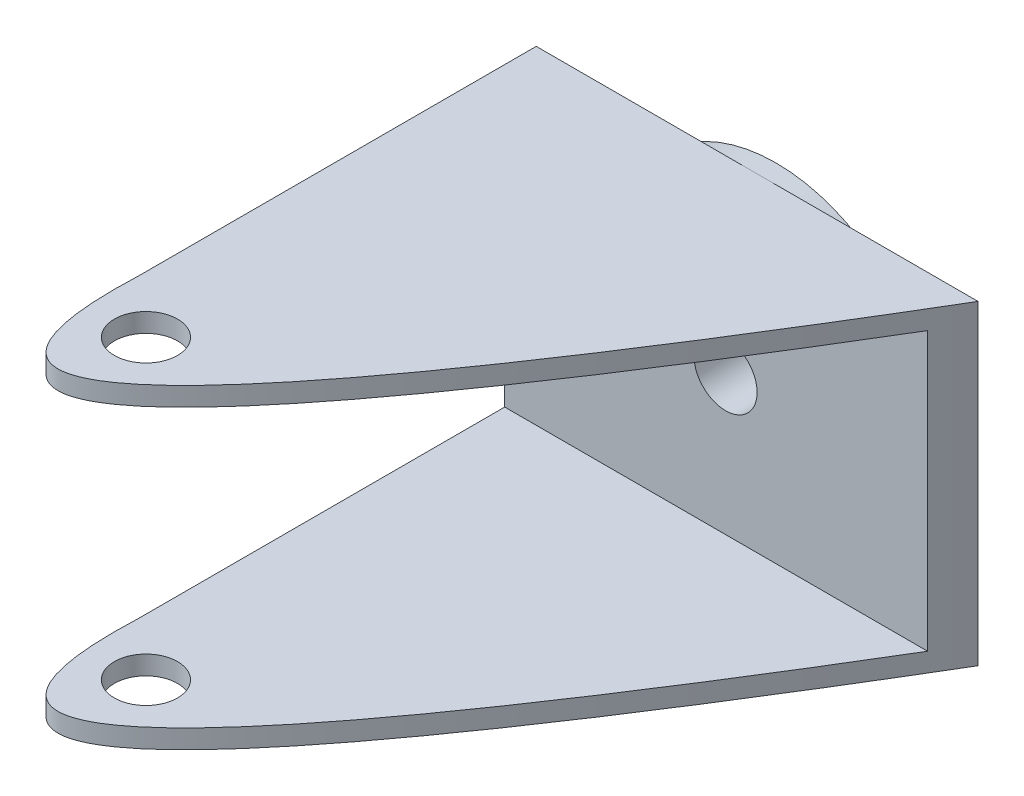
SolidWorks part; units mm, degrees
ref_plane "前视基准面" through (0, 0, 0) normal (0, 0, 1) x (1, 0, 0)
ref_plane "上视基准面" through (0, 0, 0) normal (0, 1, 0) x (1, 0, 0)
ref_plane "右视基准面" through (0, 0, 0) normal (1, 0, 0) x (0, 0, -1)
sketch "草图1" plane through (0, 0, 0) normal (0, 1, 0) x (1, 0, 0)
  line L0 (0, 0) -> (50000, 0) construction
  line L1 (0, 0) -> (0, 50000) construction
  line L2 (-23.3234, 7.2321) -> (-23.3234, 70)
  line L3 (-23.3234, 70) -> (46.6766, 70)
  spline S0 degree 2 poles (46.6766, 70) (-25.8803, -52.0544) (-23.3234, 7.2321) knots 0 0 0 1 1 1
extrude "凸台-拉伸1" add sketch "草图1" along normal blind 50
sketch "草图2" plane through (0, 50, 0) normal (0, 1, 0) x (1, 0, 0)
  line L0 (-23.3234, 7.8885) -> (-23.3234, 72.5686) construction
  line L1 (-23.3234, 70) -> (-23.3234, 7.2321) construction
  line L2 (-14.3234, -0.8457) -> (49985.6766, -0.8457) construction
  line L3 (-23.3234, 7.8885) -> (-23.3234, 50007.8885) construction
  circle A0 centre (-14.3234, -0.8457) radius 5
  dimension "D1" = 9
extrude "切除-拉伸1" cut sketch "草图2" against normal through all contours A0
sketch "草图3" plane through (0, 0, -70) normal (0, 0, -1) x (-1, 0, 0)
  line L0 (-46.6766, 25) -> (49953.3234, 25) construction
  line L1 (-46.6766, 50) -> (-46.6766, 0) construction
  line L2 (-46.6766, 25) -> (-46.6766, 50025) construction
  circle A0 centre (-21.6766, 25) radius 15
  point P4 (-46.6766, 25)
  dimension "D1" = 25
extrude "凸台-拉伸2" add sketch "草图3" along normal blind 3 contours A0
sketch "草图5" plane through (0, 0, -70) normal (0, 0, -1) x (-1, 0, 0)
  line L0 (-46.6766, 25) -> (49953.3234, 25) construction
  line L1 (-46.6766, 50) -> (-46.6766, 0) construction
  line L2 (-46.6766, 25) -> (-46.6766, 50025) construction
  circle A0 centre (-21.6766, 25) radius 5
  point P4 (-46.6766, 25)
  dimension "D1" = 25
extrude "切除-拉伸3" cut sketch "草图5" against normal up to next contours A0
sketch "草图6" plane through (0, 0, -70) normal (0, 0, 1) x (1, 0, 0)
  circle A0 centre (21.6766, 25) radius 5
extrude "切除-拉伸5" cut sketch "草图6" against normal through all contours A0
sketch "草图7" plane through (-23.3234, 0, 0) normal (-1, 0, 0) x (0, 0, 1)
  line L0 (-70, 25) -> (49930, 25) construction
  line L1 (-70, 50) -> (-70, 0) construction
  line L2 (-70, 25) -> (-70, 50025) construction
  line L3 (-70, 50) -> (-7.2321, 50) construction
  line L4 (-65, 47) -> (35, 47)
  line L5 (-65, 47) -> (-65, 3)
  line L6 (-65, 3) -> (35, 3)
  line L7 (35, 47) -> (35, 3)
  point P4 (-70, 25)
  dimension "D1" = 5
  dimension "D2" = 3
  dimension "D3" = 100
extrude "切除-拉伸7" cut sketch "草图7" against normal blind 121
sketch "草图8" plane through (-23.3234, 0, 0) normal (1, 0, 0) x (0, 0, -1)
  line L0 (0, 47) -> (0, 3)
  line L1 (0, 3) -> (7.2321, 3)
  line L2 (7.2321, 3) -> (7.2321, 47)
  line L3 (7.2321, 47) -> (0, 47)
  line L4 (0, 3) -> (0, 47)
  line L5 (7.2321, 47) -> (7.2321, 3)
  line M4 (7.2321, 47) -> (0, 47)
  line M5 (0, 47) -> (0, 3)
  line M6 (0, 3) -> (7.2321, 3)
  line M7 (7.2321, 3) -> (7.2321, 47)
extrude "切除-拉伸10" cut sketch "草图8" against normal blind 10 contours M7 M4 M5 M6
sketch "草图9" plane through (0, 0, -70) normal (0, 0, -1) x (-1, 0, 0)
  line L0 (-46.6766, 25) -> (49953.3234, 25) construction
  line L1 (-46.6766, 50) -> (-46.6766, 0) construction
  line L2 (-46.6766, 25) -> (-46.6766, 50025) construction
  line L3 (-21.6766, 0) -> (-46.6766, 0)
  line L4 (-46.6766, 0) -> (-46.6766, 50)
  line L5 (-46.6766, 50) -> (-21.6766, 50)
  circle A0 centre (-21.6766, 25) radius 25
  point P4 (-46.6766, 25)
  circle M3 centre (-21.6766, 25) radius 15
  dimension "D1" = 25
extrude "凸台-拉伸3" add sketch "草图9" along normal blind 3 contours A0 M3
sketch "草图10" plane through (0, 0, -73) normal (0, 0, -1) x (-1, 0, 0)
  circle A0 centre (-21.6766, 25) radius 5
extrude "凸台-拉伸4" add sketch "草图10" against normal blind 8 contours A0
sketch "草图11" plane through (0, 0, -70) normal (0, 0, -1) x (-1, 0, 0)
  line L1 (-46.6766, 0) -> (23.3234, 0)
  line L2 (-46.6766, 0) -> (-46.6766, 50)
  line L3 (-46.6766, 50) -> (23.3234, 50)
  line L4 (23.3234, 0) -> (23.3234, 50)
extrude "切除-拉伸11" cut sketch "草图11" along normal blind 8
sketch "草图12" plane through (0, 0, -70) normal (0, 0, -1) x (-1, 0, 0)
  line L0 (-46.6766, 25) -> (49953.3234, 25) construction
  line L1 (-46.6766, 50) -> (-46.6766, 0) construction
  line L2 (-11.6766, 0) -> (-11.6766, 50000) construction
  line L3 (-46.6766, 0) -> (23.3234, 0) construction
  circle A1 centre (-11.6766, 25) radius 25
  point P4 (-46.6766, 25)
  point P9 (-11.6766, 0)
extrude "凸台-拉伸6" add sketch "草图12" along normal blind 3 contours A1
sketch "草图19" plane through (0, 0, -70) normal (0, 0, -1) x (-1, 0, 0)
  line L0 (-46.6766, 50) -> (23.3234, 0)
  line L1 (23.3234, 50) -> (-46.6766, 0)
  circle A0 centre (-11.6766, 25) radius 5
extrude "切除-拉伸14" cut sketch "草图19" against normal mid plane 13 contours L1 A0 L0 | L0 A0 L1 | L1 A0 L0 | L0 A0 L1
scale "缩放比例1" bodies to scale 124 scale about centroid uniform scaling yes scale factor 0.5
scale "缩放比例2" bodies to scale 125 scale about centroid uniform scaling yes scale factor 1.2
